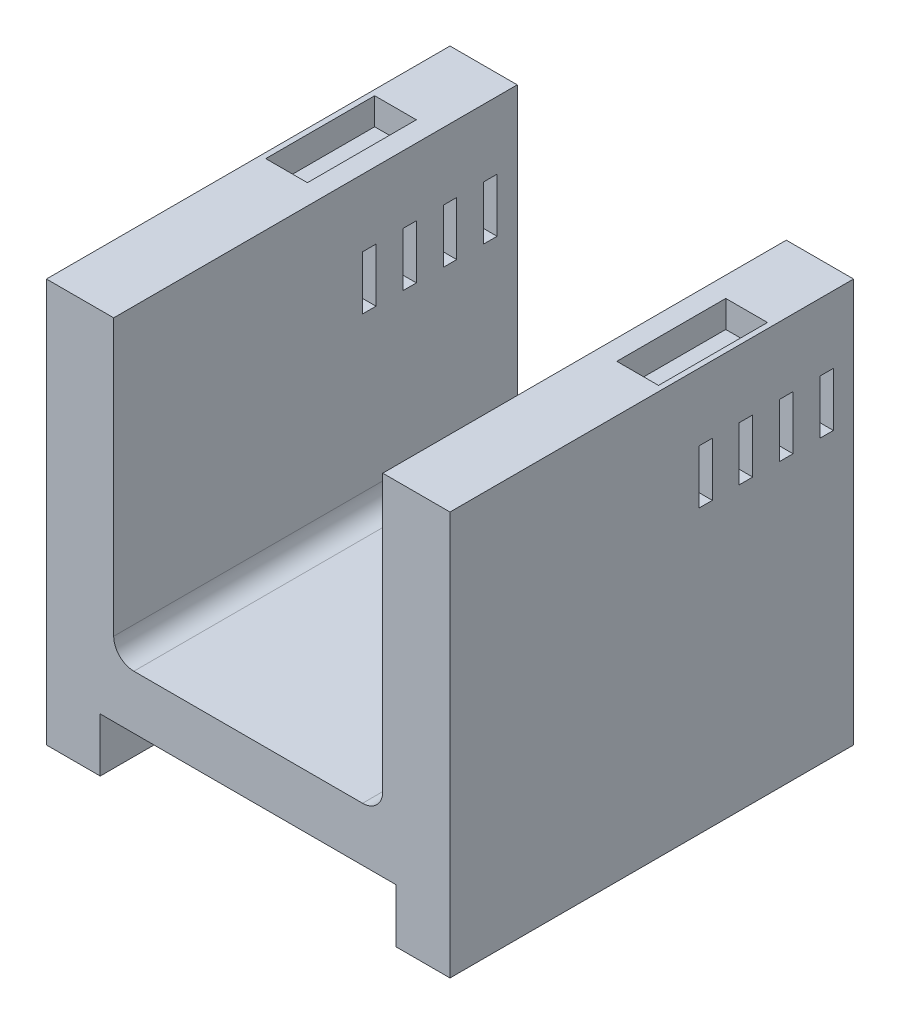
SolidWorks part; units mm, degrees
ref_plane "Front Plane" through (0, 0, 0) normal (0, 0, 1) x (1, 0, 0)
ref_plane "Top Plane" through (0, 0, 0) normal (0, 1, 0) x (1, 0, 0)
ref_plane "Right Plane" through (0, 0, 0) normal (1, 0, 0) x (0, 0, -1)
sketch "Sketch1" plane through (0, 0, 0) normal (0, 0, 1) x (1, 0, 0)
  line L1 (-75, 75) -> (75, 75)
  line L2 (-75, 75) -> (-75, -75)
  line L3 (-75, -75) -> (75, -75)
  line L4 (75, 75) -> (75, -75)
  line L5 (-75, 75) -> (75, -75) construction
  line L6 (-75, -75) -> (75, 75) construction
  point P0 (0, 0)
  dimension "D1" = 150
  dimension "D2" = 150
extrude "Boss-Extrude2" add sketch "Sketch1" along normal mid plane 150
sketch "Sketch2" plane through (0, 0, 75) normal (0, 0, 1) x (1, 0, 0)
  line L0 (-75, -75) -> (75, -75) construction
  line L1 (-55, -75) -> (55, -75)
  line L2 (-55, -75) -> (-55, -55)
  line L3 (-55, -55) -> (55, -55)
  line L4 (55, -75) -> (55, -55)
  line L5 (-55, -75) -> (55, -55) construction
  line L6 (-55, -55) -> (55, -75) construction
  line L7 (75, -75) -> (75, 75) construction
  line L8 (-75, 75) -> (-75, -75) construction
  line L9 (75, 75) -> (-75, 75) construction
  line L10 (-50, 75) -> (50, 75)
  line L11 (-50, 75) -> (-50, -35)
  line L12 (-50, -35) -> (50, -35)
  line L13 (50, 75) -> (50, -35)
  line L14 (-50, 75) -> (50, -35) construction
  line L15 (-50, -35) -> (50, 75) construction
  point P4 (0, -65)
  point P15 (0, 20)
  dimension "D1" = 20
  dimension "D2" = 20
  dimension "D3" = 20
  dimension "D4" = 25
  dimension "D5" = 25
  dimension "2" = 20
extrude "Cut-Extrude1" cut sketch "Sketch2" against normal blind 150
ref_plane "Plane1" through (0, 75, 0) normal (0, 1, 0) x (1, 0, 0)
sketch "Sketch3" plane through (0, 75, 0) normal (0, 1, 0) x (1, 0, 0)
  line L0 (-50, 75) -> (-50, -75) construction
  line L1 (-73, 45) -> (-57.5, 45)
  line L2 (-73, 45) -> (-73, 4.5)
  line L3 (-73, 4.5) -> (-57.5, 4.5)
  line L4 (-57.5, 45) -> (-57.5, 4.5)
  line L5 (-73, 45) -> (-57.5, 4.5) construction
  line L6 (-73, 4.5) -> (-57.5, 45) construction
  line L7 (57.5, 45) -> (73, 45)
  line L8 (57.5, 45) -> (57.5, 4.5)
  line L9 (57.5, 4.5) -> (73, 4.5)
  line L10 (73, 45) -> (73, 4.5)
  line L11 (57.5, 45) -> (73, 4.5) construction
  line L12 (57.5, 4.5) -> (73, 45) construction
  line L13 (50, 75) -> (50, -75) construction
  line L14 (-50, 75) -> (-75, 75) construction
  point P0 (-65.25, 24.75)
  point P5 (65.25, 24.75)
  dimension "D1" = 40.5
  dimension "D2" = 40.5
  dimension "D3" = 15.5
  dimension "D4" = 15.5
  dimension "D5" = 7.5
  dimension "D6" = 7.5
  dimension "D7" = 30
extrude "Cut-Extrude2" cut sketch "Sketch3" against normal blind 10
fillet "Fillet1" radius 7.5 2 edges at (50, -35, 0) (-50, -35, 0)
sketch "Sketch4" plane through (75, 0, 0) normal (1, 0, 0) x (0, 0, -1)
  line L0 (0, 0) -> (75, 0) construction
  line L13 (75, -75) -> (75, 75) construction
  line L42 (47.5, 50) -> (47.5, 30)
  line L43 (62.5, 50) -> (67.5, 50)
  line L44 (62.5, 50) -> (62.5, 30)
  line L45 (62.5, 30) -> (67.5, 30)
  line L46 (67.5, 50) -> (67.5, 30)
  line L47 (62.5, 50) -> (67.5, 30) construction
  line L48 (62.5, 30) -> (67.5, 50) construction
  line L49 (47.5, 50) -> (52.5, 50)
  line L50 (52.5, 50) -> (52.5, 30)
  line L51 (47.5, 30) -> (52.5, 30)
  line L52 (32.5, 50) -> (32.5, 30)
  line L53 (32.5, 50) -> (37.5, 50)
  line L54 (37.5, 50) -> (37.5, 30)
  line L55 (32.5, 30) -> (37.5, 30)
  line L56 (17.5, 50) -> (17.5, 30)
  line L57 (17.5, 50) -> (22.5, 50)
  line L58 (22.5, 50) -> (22.5, 30)
  line L59 (17.5, 30) -> (22.5, 30)
  line L60 (-75, 75) -> (75, 75) construction
  point P4 (65, 40)
  dimension "D1" = 20
  dimension "D2" = 5
  dimension "D3" = 4
  dimension "D4" = 7.5
  dimension "D5" = 35
  dimension "D6" = 10
extrude "Cut-Extrude3" cut sketch "Sketch4" against normal blind 140
sketch "Sketch5" plane through (-75, 0, 0) normal (-1, 0, 0) x (0, 0, 1)
  line L0 (-75, 0) -> (75, 0) construction
  line L1 (-75, 75) -> (-75, -75) construction
  line L2 (75, 75) -> (75, -75) construction
  text T0 "CAD" font "Times New Roman" height 5
extrude "Cut-Extrude4" cut sketch "Sketch5" against normal blind 1
equation "\"D2@Sketch2\"=\"D1@Sketch2\""
equation "\"D5@Sketch2\"=\"D4@Sketch2\""
equation "\"D2@Sketch3\"=\"D1@Sketch3\""
equation "\"D4@Sketch3\"=\"D3@Sketch3\""
